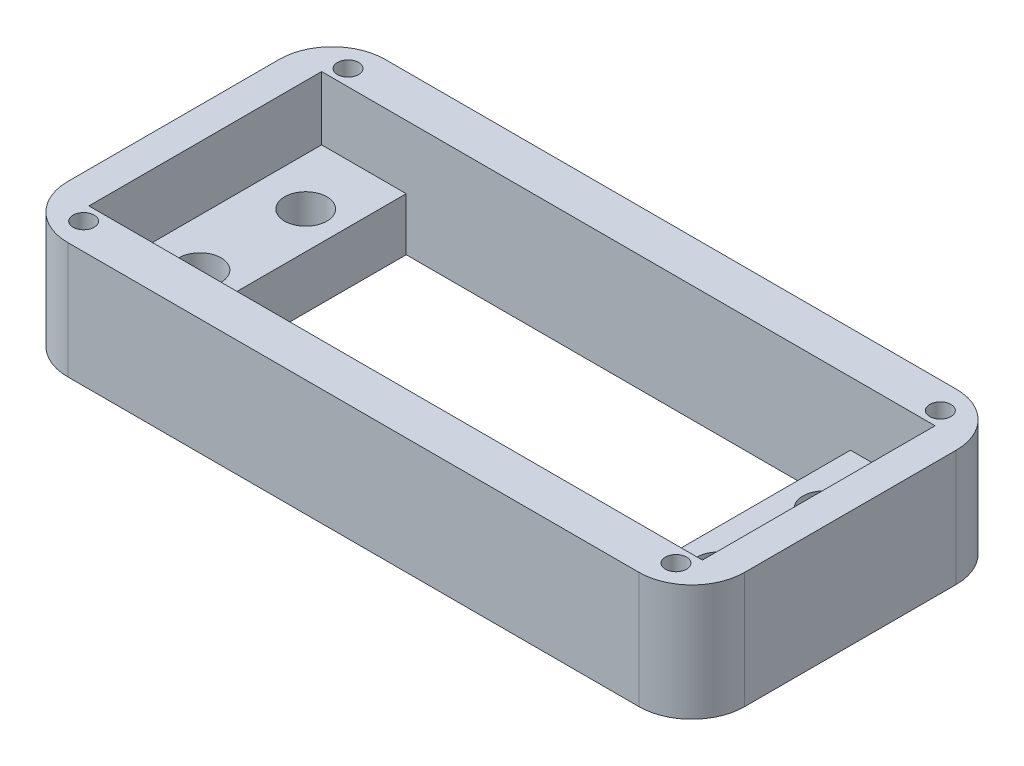
SolidWorks part; units mm, degrees
ref_plane "Front Plane" through (0, 0, 0) normal (0, 0, 1) x (1, 0, 0)
ref_plane "Top Plane" through (0, 0, 0) normal (0, 1, 0) x (1, 0, 0)
ref_plane "Right Plane" through (0, 0, 0) normal (1, 0, 0) x (0, 0, -1)
sketch "Sketch2" plane through (0, 0, 0) normal (0, 1, 0) x (1, 0, 0)
  line L1 (0, 0) -> (64, 0)
  line L2 (0, 0) -> (0, 30)
  line L3 (0, 30) -> (64, 30)
  line L4 (64, 0) -> (64, 30)
  dimension "D1" = 64
  dimension "D2" = 30
extrude "Boss-Extrude1" add sketch "Sketch2" along normal blind 64
sketch "Sketch3" plane through (0, 64, 0) normal (0, 1, 0) x (1, 0, 0)
  line L4 (0, 30) -> (0, 0) construction
  line L5 (11, 26) -> (53, 26)
  line L6 (11, 26) -> (11, 4)
  line L7 (11, 4) -> (53, 4)
  line L8 (53, 26) -> (53, 4)
  line L9 (64, 0) -> (64, 30) construction
  line L10 (0, 0) -> (64, 0) construction
  line L11 (64, 30) -> (0, 30) construction
  dimension "D1" = 11
  dimension "D2" = 11
  dimension "D3" = 4
  dimension "D4" = 4
extrude "Cut-Extrude1" cut sketch "Sketch3" against normal up to next
sketch "Sketch4" plane through (0, 64, 0) normal (0, 1, 0) x (1, 0, 0)
  line L0 (32, 30) -> (32, 0) construction
  line L1 (64, 30) -> (0, 30) construction
  line L2 (0, 0) -> (64, 0) construction
  line L3 (32, 15) -> (0, 15) construction
  line L4 (0, 30) -> (0, 0) construction
  line L5 (11, 26) -> (11, 4) construction
  circle A0 centre (7.5, 20) radius 2
  circle A2 centre (7.5, 10) radius 2
  circle A3 centre (56.5, 10) radius 2
  circle A4 centre (56.5, 20) radius 2
  dimension "D1" = 4
  dimension "D3" = 3.5
  dimension "D2" = 10
extrude "Cut-Extrude2" cut sketch "Sketch4" against normal up to next
sketch "Sketch5" plane through (0, 64, 0) normal (0, 1, 0) x (1, 0, 0)
  line L0 (3, 4) -> (61, 4)
  line L7 (3, 4) -> (3, 26)
  line L21 (3, 26) -> (61, 26)
  line L22 (61, 26) -> (61, 4)
  line L23 (53, 26) -> (11, 26) construction
  line L24 (0, 30) -> (0, 0) construction
  line L25 (64, 0) -> (64, 30) construction
  line L26 (64, 30) -> (0, 30) construction
  line L27 (0, 0) -> (64, 0) construction
  line L28 (64, 0) -> (64, 30)
  line L29 (64, 30) -> (0, 30)
  line L30 (0, 0) -> (64, 0)
  line L31 (0, 30) -> (0, 0)
  dimension "D1" = 3
  dimension "D2" = 3
extrude "Boss-Extrude2" add sketch "Sketch5" along normal blind 12
sketch "Sketch6" plane through (0, 76, 0) normal (0, 1, 0) x (1, 0, 0)
  line L0 (32, 30) -> (32, 0) construction
  line L1 (64, 30) -> (0, 30) construction
  line L2 (0, 0) -> (64, 0) construction
  line L3 (32, 15) -> (0, 15) construction
  line L4 (0, 30) -> (0, 0) construction
  circle A0 centre (4, 27.5) radius 1
  circle A1 centre (4, 2.5) radius 1
  circle A2 centre (60, 2.5) radius 1
  circle A3 centre (60, 27.5) radius 1
  dimension "D1" = 2
  dimension "D2" = 4
  dimension "D3" = 2.5
extrude "Cut-Extrude3" cut sketch "Sketch6" against normal up to next
fillet "Fillet1" radius 5 4 edges at (64, 38, -30) (64, 38, 0) (0, 38, -30) (0, 38, 0)
sketch "Sketch7" plane through (0, 0, 0) normal (0, -1, 0) x (1, 0, 0)
  line L4 (5, -30) -> (59, -30)
  line L5 (64, -25) -> (64, -5)
  line L6 (59, 0) -> (5, 0)
  line L7 (0, -5) -> (0, -25)
  line L8 (5, -30) -> (59, -30)
  line L9 (64, -25) -> (64, -5)
  line L10 (59, 0) -> (5, 0)
  line L11 (0, -5) -> (0, -25)
  arc A4 (59, -30) -> (64, -25) centre (59, -25) ccw
  arc A5 (64, -5) -> (59, 0) centre (59, -5) ccw
  arc A6 (5, 0) -> (0, -5) centre (5, -5) ccw
  arc A7 (0, -25) -> (5, -30) centre (5, -25) ccw
  arc A8 (59, -30) -> (64, -25) centre (59, -25) ccw
  arc A9 (64, -5) -> (59, 0) centre (59, -5) ccw
  arc A10 (5, 0) -> (0, -5) centre (5, -5) ccw
  arc A11 (0, -25) -> (5, -30) centre (5, -25) ccw
  dimension "D1" = 0
extrude "Cut-Extrude4" cut sketch "Sketch7" against normal offset from surface (59 mm away) 5 up to face at (7.5, 64, -12)
sketch "Sketch10" plane through (0, 76, 0) normal (0, 1, 0) x (1, 0, 0)
  line L4 (64, 5) -> (64, 25)
  line L5 (59, 30) -> (5, 30)
  line L6 (0, 25) -> (0, 5)
  line L7 (5, 0) -> (59, 0)
  line L8 (64, 5) -> (64, 25)
  line L9 (59, 30) -> (5, 30)
  line L10 (0, 25) -> (0, 5)
  line L11 (5, 0) -> (59, 0)
  arc A4 (64, 25) -> (59, 30) centre (59, 25) ccw
  arc A5 (5, 30) -> (0, 25) centre (5, 25) ccw
  arc A6 (0, 5) -> (5, 0) centre (5, 5) ccw
  arc A7 (59, 0) -> (64, 5) centre (59, 5) ccw
  arc A8 (64, 25) -> (59, 30) centre (59, 25) ccw
  arc A9 (5, 30) -> (0, 25) centre (5, 25) ccw
  arc A10 (0, 5) -> (5, 0) centre (5, 5) ccw
  arc A11 (59, 0) -> (64, 5) centre (59, 5) ccw
  dimension "D1" = 0
extrude "Cut-Extrude7" cut sketch "Sketch10" against normal blind 6
